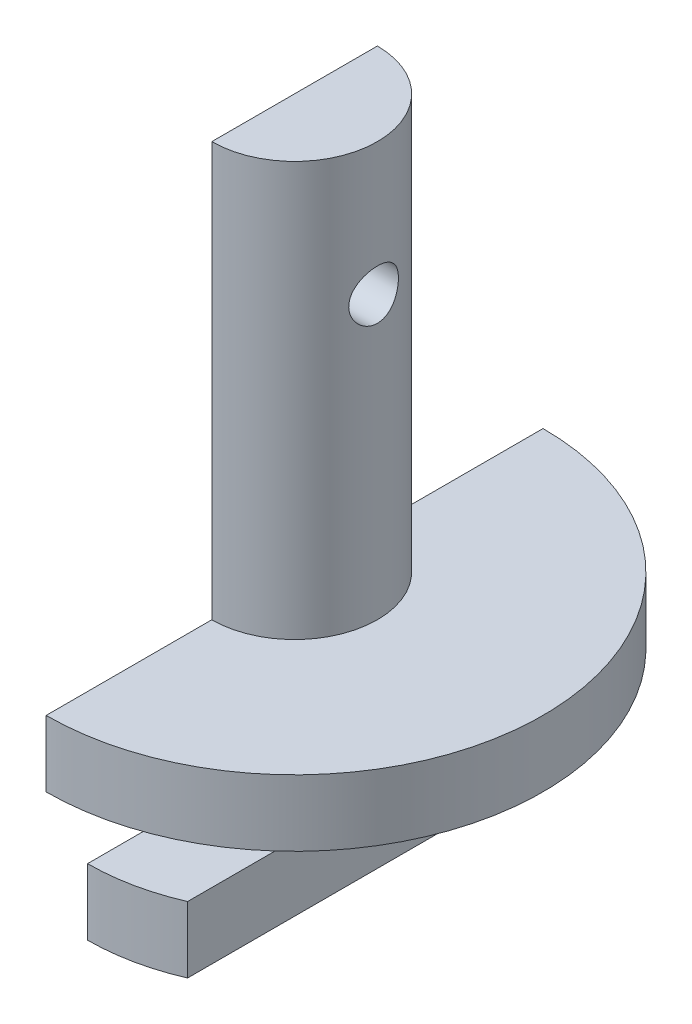
SolidWorks part; units mm, degrees
ref_plane "Front Plane" through (0, 0, 0) normal (0, 0, 1) x (1, 0, 0)
ref_plane "Top Plane" through (0, 0, 0) normal (0, 1, 0) x (1, 0, 0)
ref_plane "Right Plane" through (0, 0, 0) normal (1, 0, 0) x (0, 0, -1)
sketch "Sketch1" plane through (0, 0, 0) normal (0, 0, 1) x (1, 0, 0)
  line L0 (0, 0) -> (0, 38)
  line L1 (0, 0) -> (12.5, 0)
  line L2 (12.5, 0) -> (12.5, 4)
  line L3 (12.5, 4) -> (7.5, 4)
  line L4 (7.5, 4) -> (7.5, 9)
  line L5 (7.5, 9) -> (15, 9)
  line L6 (15, 9) -> (15, 13)
  line L7 (15, 13) -> (5, 13)
  line L8 (5, 13) -> (5, 38)
  line L9 (5, 38) -> (0, 38)
  dimension "D1" = 4
  dimension "D2" = 5
  dimension "D3" = 4
  dimension "D4" = 12.5
  dimension "D5" = 7.5
  dimension "D6" = 15
  dimension "D7" = 5
  dimension "D8" = 25
revolve "Revolve1" add sketch "Sketch1" angle 360 about L0
sketch "Sketch2" plane through (0, 0, 0) normal (0, 0, 1) x (1, 0, 0)
  line L0 (5, -5.7665) -> (26.666, -5.7665)
  line L1 (26.666, -5.7665) -> (26.666, 4)
  line L2 (26.666, 4) -> (5, 4)
  line L4 (5, 4) -> (5, -5.7665)
  dimension "D1" = 5
extrude "Cut-Extrude1" cut sketch "Sketch2" against normal through all both and the other way through all
sketch "Sketch3" plane through (0, 0, 0) normal (1, 0, 0) x (0, 0, -1)
  circle A0 centre (0, 30) radius 1.5
extrude "Cut-Extrude2" cut sketch "Sketch3" against normal through all both and the other way through all
sketch "Sketch4" plane through (0, 0, 0) normal (0, 0, 1) x (1, 0, 0)
  line L0 (0, -5.6251) -> (0, 51.1999)
  line L1 (0, 51.1999) -> (-24.2796, 51.1999)
  line L2 (-24.2796, 51.1999) -> (-24.2796, -5.6251)
  line L3 (-24.2796, -5.6251) -> (0, -5.6251)
extrude "Cut-Extrude3" cut sketch "Sketch4" against normal through all both and the other way through all
